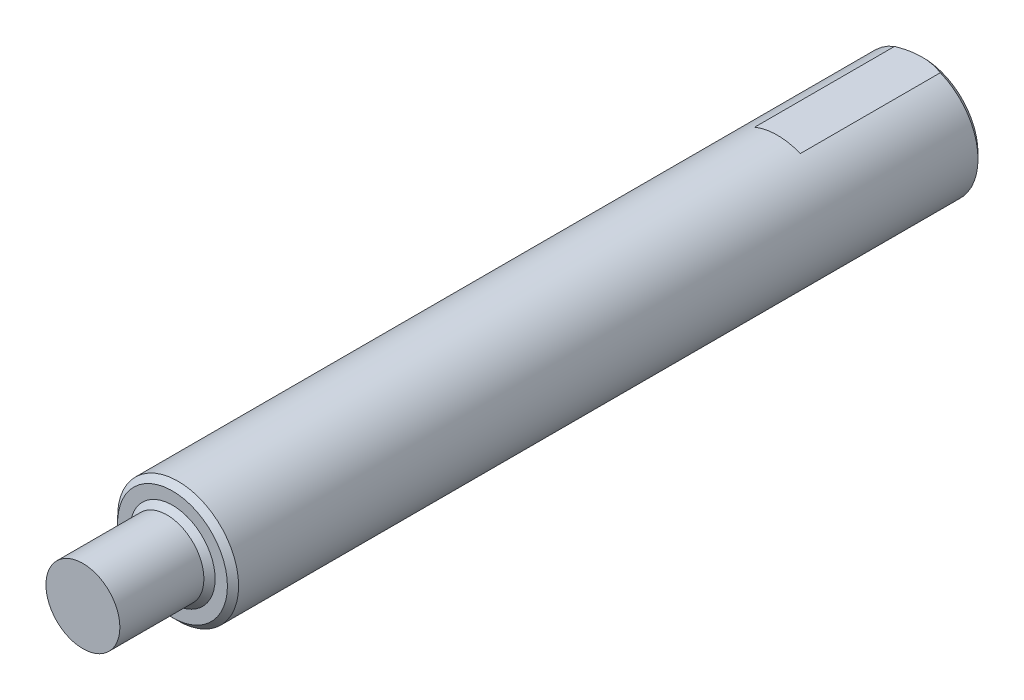
SolidWorks part; units mm, degrees
material "AISI 1045 Steel, cold drawn"
ref_plane "前视基准面" through (0, 0, 0) normal (0, 0, 1) x (1, 0, 0)
ref_plane "上视基准面" through (0, 0, 0) normal (0, 1, 0) x (1, 0, 0)
ref_plane "右视基准面" through (0, 0, 0) normal (1, 0, 0) x (0, 0, -1)
sketch "草图1" plane through (0, 0, 0) normal (0, 0, 1) x (1, 0, 0)
  circle A0 centre (0, 0) radius 5.4
  dimension "D1" = 10.8
extrude "拉伸1" add sketch "草图1" along normal blind 67
chamfer "倒角1" distance 0.5 angle 45 2 edges at (5.4, 0, 0) (5.4, 0, 67)
sketch "草图2" plane through (0, 0, 67) normal (0, 0, 1) x (1, 0, 0)
  circle A0 centre (0, 0) radius 3.3
  dimension "D1" = 6.6
extrude "拉伸2" add sketch "草图2" along normal blind 8
cosmetic thread "装饰螺纹线2" parameters "D2"=5.6
chamfer "倒角2" [suppressed] distance 0.5 angle 45
hole_wizard "M5 螺纹孔1" positions "草图4" profile "草图3" tap size "M5" standard "GB"
sketch "草图4" plane through (0, 0, 0) normal (0, 0, -1) x (-1, 0, 0)
  point P1 (0, 0)
cosmetic thread "孔螺蚊线1" parameters "D1"=10, "D2"=5
sketch "草图3" plane through (0, 0, 0) normal (1, 0, 0) x (0, 1, 0)
  line L0 (0, 0) -> (0, 13.6618)
  line L1 (0, 13.6618) -> (2.1, 12.4)
  line L2 (2.1, 12.4) -> (2.1, 0)
  line L5 (2.1, 0) -> (0, 0)
  line L10 (0, 13.6618) -> (-2.1, 12.4) construction
  line L11 (0, -6.35) -> (0, 107.95) construction
  dimension "螺纹孔钻头直径" = 4.2
  dimension "螺纹孔钻头深度" = 12.4
  dimension "导头角度" = 118
chamfer "倒角3" distance 0.5 angle 45 1 edges at (-2.1, 0, 0)
sketch "草图5" plane through (0, 0, 0) normal (0, 0, 1) x (1, 0, 0)
  line L0 (0, 0) -> (0, 5) construction
  line L1 (-5, 8) -> (5, 8)
  line L2 (-5, 8) -> (-5, 5)
  line L3 (-5, 5) -> (5, 5)
  line L4 (5, 8) -> (5, 5)
  dimension "D1" = 5
  dimension "D2" = 3
  dimension "D3" = 10
extrude "拉伸3" cut sketch "草图5" along normal blind 13
mirror "镜向1" about plane through (0, 0, 0) normal (0, 1, 0) of "拉伸3"
chamfer "倒角4" distance 0.5 angle 45 1 edges at (3.3, 0, 67)
